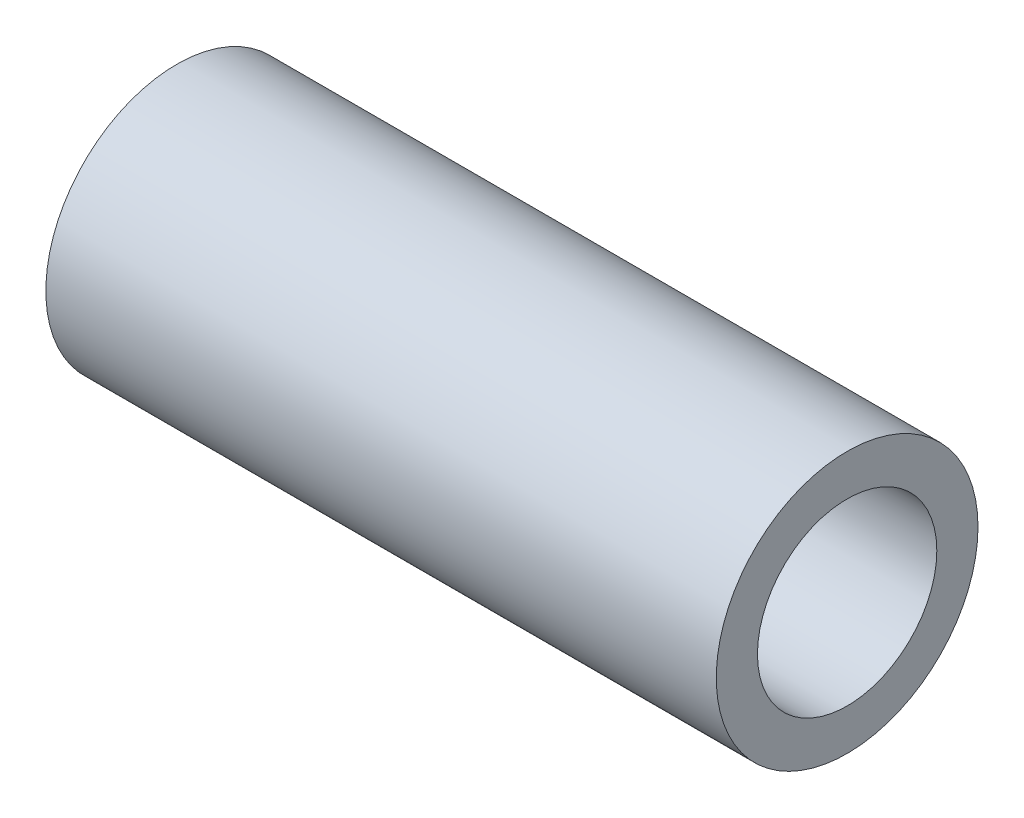
SolidWorks part; units mm, degrees
ref_plane "Front Plane" through (0, 0, 0) normal (0, 0, 1) x (1, 0, 0)
ref_plane "Top Plane" through (0, 0, 0) normal (0, 1, 0) x (1, 0, 0)
ref_plane "Right Plane" through (0, 0, 0) normal (1, 0, 0) x (0, 0, -1)
sketch "Sketch1" plane through (0, 0, 0) normal (1, 0, 0) x (0, 0, -1)
  circle A0 centre (0, 0) radius 4.7625
  circle A1 centre (0, 0) radius 3.2639
  dimension "D1" = 6.5278
  dimension "D2" = 9.525
extrude "Boss-Extrude1" add sketch "Sketch1" along normal blind 24.3967
